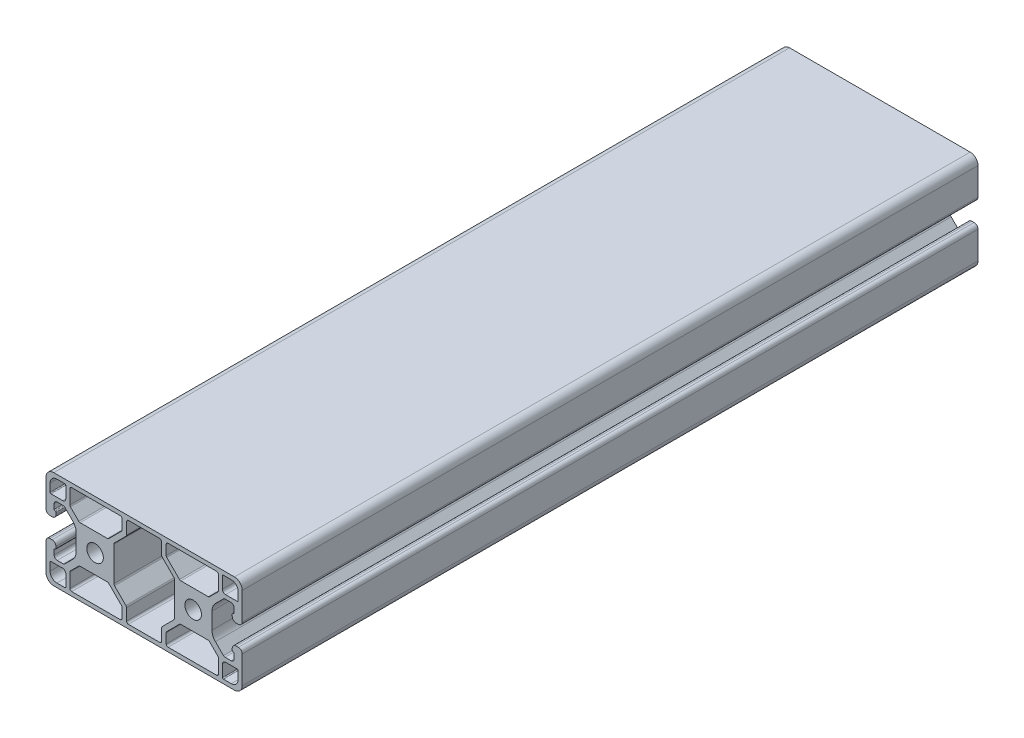
SolidWorks part; units mm, degrees
material "6105-T5 Aluminum"
ref_plane "Front Plane" through (0, 0, 0) normal (0, 0, 1) x (1, 0, 0)
ref_plane "Top Plane" through (0, 0, 0) normal (0, 1, 0) x (1, 0, 0)
ref_plane "Right Plane" through (0, 0, 0) normal (1, 0, 0) x (0, 0, -1)
sketch "Sketch1" plane through (0, 0, 0) normal (0, 0, 1) x (1, 0, 0)
  line L0 (-52.3165, -18.3492) -> (-55.5555, -18.3492)
  line L1 (-58.3495, -15.5552) -> (-58.3495, -12.3165)
  line L2 (-57.9695, -11.9365) -> (-53.2063, -11.9365)
  line L3 (-51.9365, -13.2063) -> (-51.9365, -17.9693)
  line L4 (-55.5555, 18.3492) -> (-52.3165, 18.3492)
  line L5 (-51.9365, 17.9693) -> (-51.9365, 13.2063)
  line L6 (-53.2063, 11.9365) -> (-57.9695, 11.9365)
  line L7 (-58.3495, 12.3165) -> (-58.3495, 15.5552)
  line L8 (15.5555, -18.3492) -> (12.3165, -18.3492)
  line L9 (11.9365, -17.9693) -> (11.9365, -13.2063)
  line L10 (13.2063, -11.9365) -> (17.9695, -11.9365)
  line L11 (18.3495, -12.3165) -> (18.3495, -15.5552)
  line L12 (12.3165, 18.3492) -> (15.5555, 18.3492)
  line L13 (18.3495, 15.5552) -> (18.3495, 12.3165)
  line L14 (17.9695, 11.9365) -> (13.2063, 11.9365)
  line L15 (11.9365, 13.2063) -> (11.9365, 17.9693)
  line L16 (-10.2222, 18.3492) -> (9.5238, 18.3492)
  line L17 (10.2857, 17.5873) -> (10.2857, 11.8584)
  line L18 (10.0626, 11.3196) -> (6.6486, 7.9057)
  line L19 (6.1099, 7.6825) -> (-5.0324, 7.6825)
  line L20 (-5.5711, 7.9057) -> (-10.761, 13.0955)
  line L21 (-10.9841, 13.6343) -> (-10.9841, 17.5873)
  line L22 (-46.1099, -7.6825) -> (-34.9676, -7.6825)
  line L23 (-34.4289, -7.9057) -> (-29.239, -13.0955)
  line L24 (-29.0159, -13.6343) -> (-29.0159, -17.5873)
  line L25 (-29.7778, -18.3492) -> (-49.5238, -18.3492)
  line L26 (-50.2857, -17.5873) -> (-50.2857, -11.8584)
  line L27 (-50.0626, -11.3196) -> (-46.6486, -7.9057)
  line L28 (-46.6486, 7.9057) -> (-50.0626, 11.3196)
  line L29 (-50.2857, 11.8584) -> (-50.2857, 17.5873)
  line L30 (-49.5238, 18.3492) -> (-29.7778, 18.3492)
  line L31 (-29.0159, 17.5873) -> (-29.0159, 13.6343)
  line L32 (-29.239, 13.0955) -> (-34.4289, 7.9057)
  line L33 (-34.9676, 7.6825) -> (-46.1099, 7.6825)
  line L34 (-10.761, -13.0955) -> (-5.5711, -7.9057)
  line L35 (-5.0324, -7.6825) -> (6.1099, -7.6825)
  line L36 (6.6486, -7.9057) -> (10.0626, -11.3196)
  line L37 (10.2857, -11.8584) -> (10.2857, -17.5873)
  line L38 (9.5238, -18.3492) -> (-10.2222, -18.3492)
  line L39 (-10.9841, -17.5873) -> (-10.9841, -13.6343)
  line L40 (-27.435, -12.2058) -> (-32.0571, -7.5838)
  line L41 (-32.3175, -6.9551) -> (-32.3175, 7.0078)
  line L42 (-32.0943, 7.5465) -> (-27.3343, 12.3066)
  line L43 (-27.1111, 12.8453) -> (-27.1111, 17.5873)
  line L44 (-26.3492, 18.3492) -> (-13.6508, 18.3492)
  line L45 (-12.8889, 17.5873) -> (-12.8889, 12.8453)
  line L46 (-12.6657, 12.3066) -> (-7.9057, 7.5465)
  line L47 (-7.6825, 7.0078) -> (-7.6825, -6.9551)
  line L48 (-7.9429, -7.5838) -> (-12.565, -12.2058)
  line L49 (-12.8254, -12.8345) -> (-12.8254, -17.5873)
  line L50 (-13.5873, -18.3492) -> (-26.4127, -18.3492)
  line L51 (-27.1746, -17.5873) -> (-27.1746, -12.8345)
  line L52 (15.4286, -10.2857) -> (12.9885, -10.2857)
  line L53 (12.3599, -10.0254) -> (9.0736, -6.739)
  line L54 (7.6825, -3.3808) -> (7.6825, 3.3808)
  line L55 (9.0736, 6.739) -> (12.3599, 10.0254)
  line L56 (12.9885, 10.2857) -> (15.4286, 10.2857)
  line L57 (16.6984, 9.0159) -> (16.6984, 7.1685)
  line L58 (16.3317, 6.7888) -> (16.3032, 6.7878)
  line L59 (15.9365, 6.4081) -> (15.9365, 5.6381)
  line L60 (17.5111, 4.0635) -> (18.4254, 4.0635)
  line L61 (20, 5.6381) -> (20, 16.8254)
  line L62 (16.8254, 20) -> (-56.8254, 20)
  line L63 (-60, 16.8254) -> (-60, 5.6381)
  line L64 (-58.4254, 4.0635) -> (-57.5111, 4.0635)
  line L65 (-55.9365, 5.6381) -> (-55.9365, 6.3446)
  line L66 (-56.3032, 6.7243) -> (-56.3317, 6.7253)
  line L67 (-56.6984, 7.105) -> (-56.6984, 9.0159)
  line L68 (-55.4286, 10.2857) -> (-52.9885, 10.2857)
  line L69 (-52.3599, 10.0254) -> (-49.0736, 6.739)
  line L70 (-47.6825, 3.3808) -> (-47.6825, -3.3808)
  line L71 (-49.0736, -6.739) -> (-52.3599, -10.0254)
  line L72 (-52.9885, -10.2857) -> (-55.4286, -10.2857)
  line L73 (-56.6984, -9.0159) -> (-56.6984, -7.105)
  line L74 (-56.3317, -6.7253) -> (-56.3032, -6.7243)
  line L75 (-55.9365, -6.3446) -> (-55.9365, -5.6381)
  line L76 (-57.5111, -4.0635) -> (-58.4254, -4.0635)
  line L77 (-60, -5.6381) -> (-60, -16.8254)
  line L78 (-56.8254, -20) -> (16.8254, -20)
  line L79 (20, -16.8254) -> (20, -5.6381)
  line L80 (18.4254, -4.0635) -> (17.5111, -4.0635)
  line L81 (15.9365, -5.6381) -> (15.9365, -6.4081)
  line L82 (16.3032, -6.7878) -> (16.3317, -6.7888)
  line L83 (16.6984, -7.1685) -> (16.6984, -9.0159)
  arc A0 (-58.3495, -15.5552) -> (-55.5555, -18.3492) centre (-55.5555, -15.5552) ccw
  arc A1 (-57.9695, -11.9365) -> (-58.3495, -12.3165) centre (-57.9695, -12.3165) ccw
  arc A2 (-51.9365, -13.2063) -> (-53.2063, -11.9365) centre (-53.2063, -13.2063) ccw
  arc A3 (-52.3165, -18.3492) -> (-51.9365, -17.9693) centre (-52.3165, -17.9693) ccw
  arc A4 (-51.9365, 17.9693) -> (-52.3165, 18.3492) centre (-52.3165, 17.9693) ccw
  arc A5 (-53.2063, 11.9365) -> (-51.9365, 13.2063) centre (-53.2063, 13.2063) ccw
  arc A6 (-58.3495, 12.3165) -> (-57.9695, 11.9365) centre (-57.9695, 12.3165) ccw
  arc A7 (-55.5555, 18.3492) -> (-58.3495, 15.5552) centre (-55.5555, 15.5552) ccw
  arc A8 (11.9365, -17.9693) -> (12.3165, -18.3492) centre (12.3165, -17.9693) ccw
  arc A9 (13.2063, -11.9365) -> (11.9365, -13.2063) centre (13.2063, -13.2063) ccw
  arc A10 (18.3495, -12.3165) -> (17.9695, -11.9365) centre (17.9695, -12.3165) ccw
  arc A11 (15.5555, -18.3492) -> (18.3495, -15.5552) centre (15.5555, -15.5552) ccw
  arc A12 (18.3495, 15.5552) -> (15.5555, 18.3492) centre (15.5555, 15.5552) ccw
  arc A13 (17.9695, 11.9365) -> (18.3495, 12.3165) centre (17.9695, 12.3165) ccw
  arc A14 (11.9365, 13.2063) -> (13.2063, 11.9365) centre (13.2063, 13.2063) ccw
  arc A15 (12.3165, 18.3492) -> (11.9365, 17.9693) centre (12.3165, 17.9693) ccw
  arc A16 (-10.2222, 18.3492) -> (-10.9841, 17.5873) centre (-10.2222, 17.5873) ccw
  arc A17 (10.2857, 17.5873) -> (9.5238, 18.3492) centre (9.5238, 17.5873) ccw
  arc A18 (10.0626, 11.3196) -> (10.2857, 11.8584) centre (9.5238, 11.8584) ccw
  arc A19 (6.1099, 7.6825) -> (6.6486, 7.9057) centre (6.1099, 8.4444) ccw
  arc A20 (-5.5711, 7.9057) -> (-5.0324, 7.6825) centre (-5.0324, 8.4444) ccw
  arc A21 (-10.9841, 13.6343) -> (-10.761, 13.0955) centre (-10.2222, 13.6343) ccw
  arc A22 (-46.1099, -7.6825) -> (-46.6486, -7.9057) centre (-46.1099, -8.4444) ccw
  arc A23 (-34.4289, -7.9057) -> (-34.9676, -7.6825) centre (-34.9676, -8.4444) ccw
  arc A24 (-29.0159, -13.6343) -> (-29.239, -13.0955) centre (-29.7778, -13.6343) ccw
  arc A25 (-29.7778, -18.3492) -> (-29.0159, -17.5873) centre (-29.7778, -17.5873) ccw
  arc A26 (-50.2857, -17.5873) -> (-49.5238, -18.3492) centre (-49.5238, -17.5873) ccw
  arc A27 (-50.0626, -11.3196) -> (-50.2857, -11.8584) centre (-49.5238, -11.8584) ccw
  arc A28 (-46.6486, 7.9057) -> (-46.1099, 7.6825) centre (-46.1099, 8.4444) ccw
  arc A29 (-50.2857, 11.8584) -> (-50.0626, 11.3196) centre (-49.5238, 11.8584) ccw
  arc A30 (-49.5238, 18.3492) -> (-50.2857, 17.5873) centre (-49.5238, 17.5873) ccw
  arc A31 (-29.0159, 17.5873) -> (-29.7778, 18.3492) centre (-29.7778, 17.5873) ccw
  arc A32 (-29.239, 13.0955) -> (-29.0159, 13.6343) centre (-29.7778, 13.6343) ccw
  arc A33 (-34.9676, 7.6825) -> (-34.4289, 7.9057) centre (-34.9676, 8.4444) ccw
  arc A34 (-5.0324, -7.6825) -> (-5.5711, -7.9057) centre (-5.0324, -8.4444) ccw
  arc A35 (6.6486, -7.9057) -> (6.1099, -7.6825) centre (6.1099, -8.4444) ccw
  arc A36 (10.2857, -11.8584) -> (10.0626, -11.3196) centre (9.5238, -11.8584) ccw
  arc A37 (9.5238, -18.3492) -> (10.2857, -17.5873) centre (9.5238, -17.5873) ccw
  arc A38 (-10.9841, -17.5873) -> (-10.2222, -18.3492) centre (-10.2222, -17.5873) ccw
  arc A39 (-10.761, -13.0955) -> (-10.9841, -13.6343) centre (-10.2222, -13.6343) ccw
  arc A40 (-32.3175, -6.9551) -> (-32.0571, -7.5838) centre (-31.4285, -6.9551) ccw
  arc A41 (-32.0943, 7.5465) -> (-32.3175, 7.0078) centre (-31.5556, 7.0078) ccw
  arc A42 (-27.3343, 12.3066) -> (-27.1111, 12.8453) centre (-27.873, 12.8453) ccw
  arc A43 (-26.3492, 18.3492) -> (-27.1111, 17.5873) centre (-26.3492, 17.5873) ccw
  arc A44 (-12.8889, 17.5873) -> (-13.6508, 18.3492) centre (-13.6508, 17.5873) ccw
  arc A45 (-12.8889, 12.8453) -> (-12.6657, 12.3066) centre (-12.127, 12.8453) ccw
  arc A46 (-7.6825, 7.0078) -> (-7.9057, 7.5465) centre (-8.4444, 7.0078) ccw
  arc A47 (-7.9429, -7.5838) -> (-7.6825, -6.9551) centre (-8.5715, -6.9551) ccw
  arc A48 (-12.565, -12.2058) -> (-12.8254, -12.8345) centre (-11.9364, -12.8345) ccw
  arc A49 (-13.5873, -18.3492) -> (-12.8254, -17.5873) centre (-13.5873, -17.5873) ccw
  arc A50 (-27.1746, -17.5873) -> (-26.4127, -18.3492) centre (-26.4127, -17.5873) ccw
  arc A51 (-27.1746, -12.8345) -> (-27.435, -12.2058) centre (-28.0636, -12.8345) ccw
  circle A52 centre (0, 0) radius 3.3778
  circle A53 centre (-40, 0) radius 3.3778
  arc A54 (15.4286, -10.2857) -> (16.6984, -9.0159) centre (15.4286, -9.0159) ccw
  arc A55 (12.3599, -10.0254) -> (12.9885, -10.2857) centre (12.9885, -9.3968) ccw
  arc A56 (7.6825, -3.3808) -> (9.0736, -6.739) centre (12.4317, -3.3808) ccw
  arc A57 (9.0736, 6.739) -> (7.6825, 3.3808) centre (12.4317, 3.3808) ccw
  arc A58 (12.9885, 10.2857) -> (12.3599, 10.0254) centre (12.9885, 9.3968) ccw
  arc A59 (16.6984, 9.0159) -> (15.4286, 10.2857) centre (15.4286, 9.0159) ccw
  arc A60 (16.3317, 6.7888) -> (16.6984, 7.1685) centre (16.3185, 7.1685) ccw
  arc A61 (16.3032, 6.7878) -> (15.9365, 6.4081) centre (16.3165, 6.4081) ccw
  arc A62 (15.9365, 5.6381) -> (17.5111, 4.0635) centre (17.5111, 5.6381) ccw
  arc A63 (18.4254, 4.0635) -> (20, 5.6381) centre (18.4254, 5.6381) ccw
  arc A64 (20, 16.8254) -> (16.8254, 20) centre (16.8254, 16.8254) ccw
  arc A65 (-56.8254, 20) -> (-60, 16.8254) centre (-56.8254, 16.8254) ccw
  arc A66 (-60, 5.6381) -> (-58.4254, 4.0635) centre (-58.4254, 5.6381) ccw
  arc A67 (-57.5111, 4.0635) -> (-55.9365, 5.6381) centre (-57.5111, 5.6381) ccw
  arc A68 (-55.9365, 6.3446) -> (-56.3032, 6.7243) centre (-56.3165, 6.3446) ccw
  arc A69 (-56.6984, 7.105) -> (-56.3317, 6.7253) centre (-56.3185, 7.105) ccw
  arc A70 (-55.4286, 10.2857) -> (-56.6984, 9.0159) centre (-55.4286, 9.0159) ccw
  arc A71 (-52.3599, 10.0254) -> (-52.9885, 10.2857) centre (-52.9885, 9.3968) ccw
  arc A72 (-47.6825, 3.3808) -> (-49.0736, 6.739) centre (-52.4317, 3.3808) ccw
  arc A73 (-49.0736, -6.739) -> (-47.6825, -3.3808) centre (-52.4317, -3.3808) ccw
  arc A74 (-52.9885, -10.2857) -> (-52.3599, -10.0254) centre (-52.9885, -9.3968) ccw
  arc A75 (-56.6984, -9.0159) -> (-55.4286, -10.2857) centre (-55.4286, -9.0159) ccw
  arc A76 (-56.3317, -6.7253) -> (-56.6984, -7.105) centre (-56.3185, -7.105) ccw
  arc A77 (-56.3032, -6.7243) -> (-55.9365, -6.3446) centre (-56.3165, -6.3446) ccw
  arc A78 (-55.9365, -5.6381) -> (-57.5111, -4.0635) centre (-57.5111, -5.6381) ccw
  arc A79 (-58.4254, -4.0635) -> (-60, -5.6381) centre (-58.4254, -5.6381) ccw
  arc A80 (-60, -16.8254) -> (-56.8254, -20) centre (-56.8254, -16.8254) ccw
  arc A81 (16.8254, -20) -> (20, -16.8254) centre (16.8254, -16.8254) ccw
  arc A82 (20, -5.6381) -> (18.4254, -4.0635) centre (18.4254, -5.6381) ccw
  arc A83 (17.5111, -4.0635) -> (15.9365, -5.6381) centre (17.5111, -5.6381) ccw
  arc A84 (15.9365, -6.4081) -> (16.3032, -6.7878) centre (16.3165, -6.4081) ccw
  arc A85 (16.6984, -7.1685) -> (16.3317, -6.7888) centre (16.3185, -7.1685) ccw
extrude "Extrude1" add sketch "Sketch1" against normal blind 300
